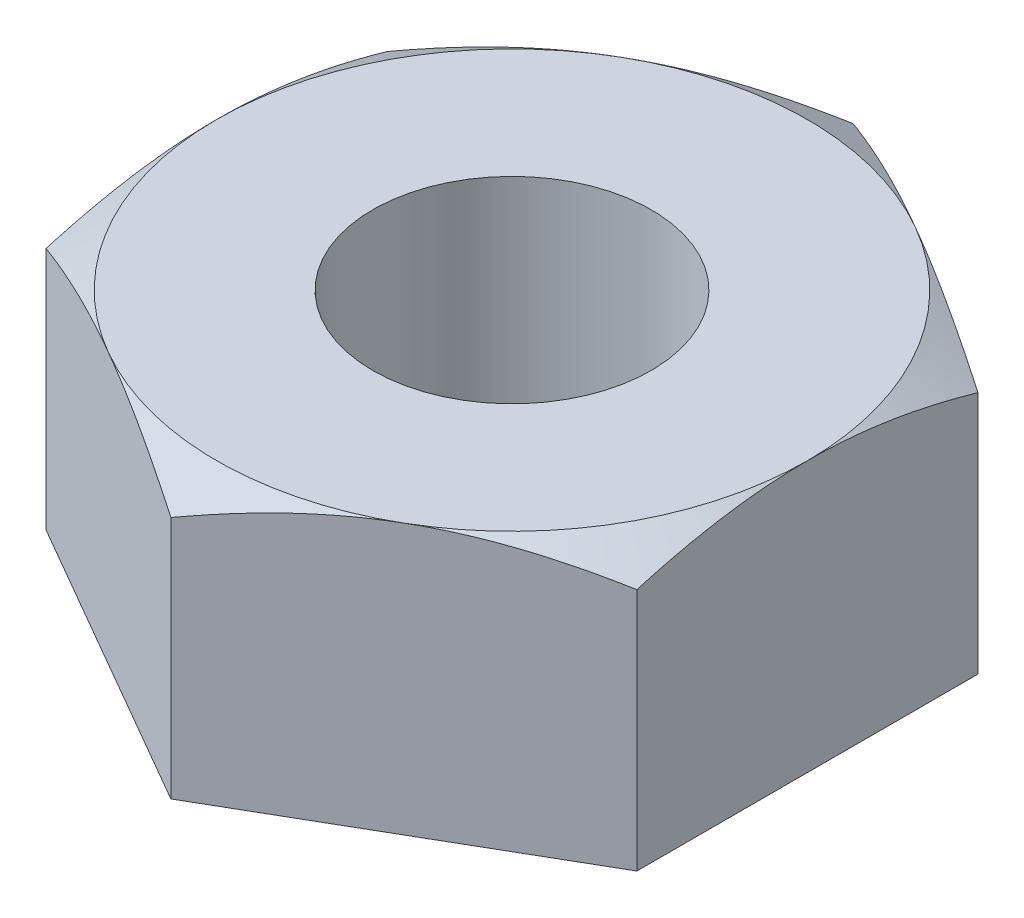
SolidWorks part; units mm, degrees
ref_plane "Front Plane" through (0, 0, 0) normal (0, 0, 1) x (1, 0, 0)
ref_plane "Top Plane" through (0, 0, 0) normal (0, 1, 0) x (1, 0, 0)
ref_plane "Right Plane" through (0, 0, 0) normal (1, 0, 0) x (0, 0, -1)
sketch "Sketch1" plane through (0, 0, 0) normal (0, 1, 0) x (1, 0, 0)
  line L1 (0, 4.0415) -> (-3.5, 2.0207)
  line L2 (-3.5, 2.0207) -> (-3.5, -2.0207)
  line L3 (-3.5, -2.0207) -> (0, -4.0415)
  line L4 (0, -4.0415) -> (3.5, -2.0207)
  line L5 (3.5, -2.0207) -> (3.5, 2.0207)
  line L6 (3.5, 2.0207) -> (0, 4.0415)
  circle A0 centre (0, 0) radius 3.5 construction
  dimension "NT_S" = 7
extrude "Boss-Extrude1" add sketch "Sketch1" against normal blind 3.2
sketch "Sketch2" plane through (0, 0, 0) normal (1, 0, 0) x (0, 0, -1)
  line L0 (0, 0) -> (0, -3.2) construction
  line L1 (-2.0207, -3.2) -> (2.0207, -3.2) construction
  line L2 (3.5, 0) -> (4.0415, 0)
  line L3 (4.0415, 0) -> (4.0415, -0.3126)
  line L4 (4.0415, -0.3126) -> (3.5, 0)
  line L5 (2.0207, 0) -> (4.0415, 0) construction
  line L6 (4.0415, -3.2) -> (4.0415, 0) construction
  dimension "D1" = 30
revolve "Cut-Revolve1" cut sketch "Sketch2" angle 360 about L0
hole_wizard "Tapped Hole1" positions "Sketch4" profile "Sketch3" tap size "M4x0.7" standard "JIS" end condition through all
sketch "Sketch4" plane through (0, 0, 0) normal (0, 1, 0) x (1, 0, 0)
  point P0 (0, 0)
sketch "Sketch3" plane through (0, 0, 0) normal (1, 0, 0) x (0, 0, 1)
  line L0 (0, 0) -> (0, 3.2)
  line L1 (0, 3.2) -> (1.65, 3.2)
  line L2 (1.65, 3.2) -> (1.65, 0)
  line L5 (1.65, 0) -> (0, 0)
  line L11 (0, 0) -> (0, 3.2) construction
  dimension "Thru Tap Drill Dia." = 3.3
  dimension "Thru Tap Drill Depth" = 3.2
cosmetic thread "Hole Thread1" parameters "NT_M"=4
